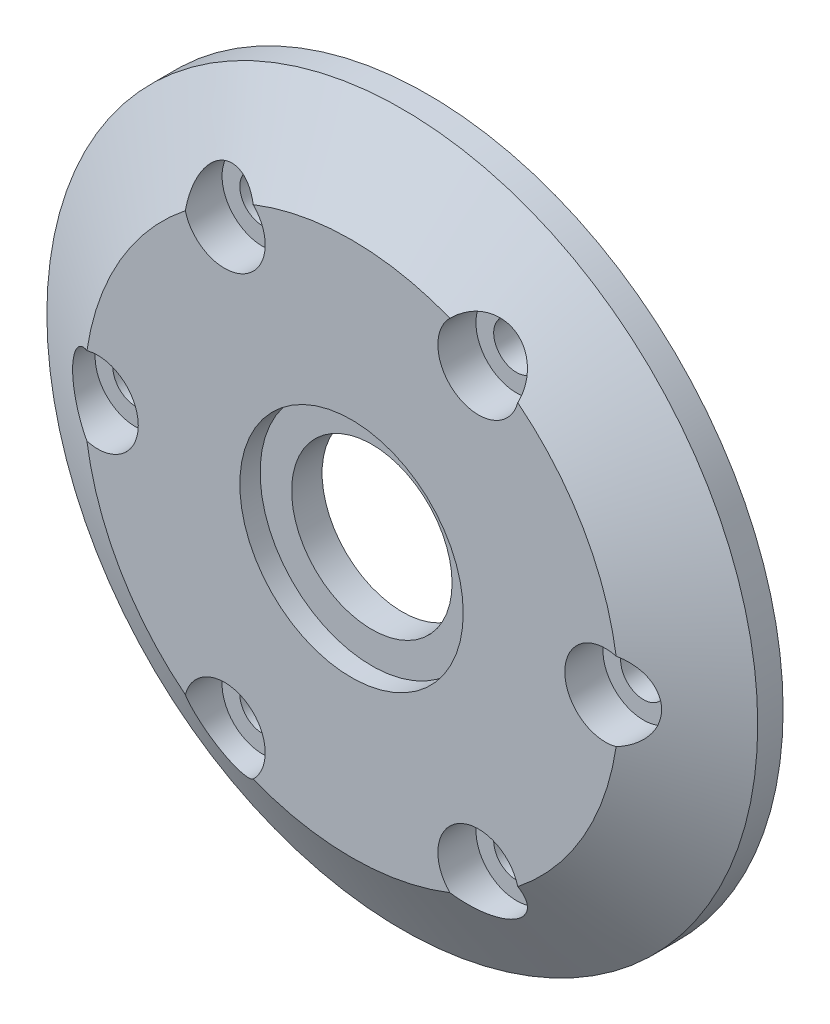
SolidWorks part; units mm, degrees
material "AISI 304"
ref_plane "Front Plane" through (0, 0, 0) normal (0, 0, 1) x (1, 0, 0)
ref_plane "Top Plane" through (0, 0, 0) normal (0, 1, 0) x (1, 0, 0)
ref_plane "Right Plane" through (0, 0, 0) normal (1, 0, 0) x (0, 0, -1)
sketch "Sketch1" plane through (0, 0, 0) normal (0, 0, 1) x (1, 0, 0)
  circle A0 centre (0, 37.5) radius 35
  dimension "D1" = 70
extrude "Boss-Extrude1" add sketch "Sketch1" along normal blind 5 draft 60
sketch "Sketch3" plane through (0, 0, 5) normal (0, 0, 1) x (1, 0, 0)
  circle A0 centre (0, 37.5) radius 11
  dimension "D1" = 22
extrude "Cut-Extrude1" cut sketch "Sketch3" against normal blind 2
sketch "Sketch4" plane through (0, 0, 5) normal (0, 0, 1) x (1, 0, 0)
  circle A0 centre (0, 37.5) radius 7.9
  dimension "D1" = 15.8
extrude "Cut-Extrude2" cut sketch "Sketch4" against normal through all
sketch "Sketch7" plane through (0, 0, 0) normal (0, 0, 1) x (1, 0, 0)
  circle A0 centre (0, 37.5) radius 35 construction
  circle A1 centre (0, 37.5) radius 12.95
  circle A2 centre (0, 37.5) radius 12.95
  circle A3 centre (0, 37.5) radius 35
  dimension "D1" = 0
extrude "Boss-Extrude2" add sketch "Sketch7" against normal blind 2.5
sketch "Sketch5" plane through (0, 0, 0) normal (0, 0, 1) x (1, 0, 0)
  circle A1 centre (-12.5, 15.8494) radius 2.25
  circle A2 centre (-12.5, 15.8494) radius 2.25
  circle A3 centre (-25, 37.5) radius 2.25
  circle A4 centre (-25, 37.5) radius 2.25
  circle A5 centre (-12.5, 59.1506) radius 2.25
  circle A6 centre (-12.5, 59.1506) radius 2.25
  circle A7 centre (12.5, 59.1506) radius 2.25
  circle A8 centre (12.5, 59.1506) radius 2.25
  circle A9 centre (25, 37.5) radius 2.25
  circle A10 centre (25, 37.5) radius 2.25
  circle A11 centre (12.5, 15.8494) radius 2.25
  circle A12 centre (12.5, 15.8494) radius 2.25
  dimension "D1" = 0
  dimension "D2" = 0
  dimension "D3" = 0
  dimension "D4" = 0
  dimension "D5" = 0
  dimension "D6" = 0
extrude "Cut-Extrude6" cut sketch "Sketch5" along normal through all and the other way through all
sketch "Sketch6" plane through (0, 0, 0) normal (0, 0, 1) x (1, 0, 0)
  circle A1 centre (0, 37.5) radius 12.95
  circle A2 centre (0, 37.5) radius 12.95
  circle A3 centre (0, 37.5) radius 11.9
  circle A4 centre (0, 37.5) radius 11.9
  dimension "D1" = 0
  dimension "D2" = 0
extrude "Cut-Extrude7" [suppressed] cut sketch "Sketch6" along normal blind 2.5
sketch "Sketch8" plane through (0, 0, 5) normal (0, 0, 1) x (1, 0, 0)
  circle A1 centre (-12.5, 59.1506) radius 4
  arc A2 (-27.2656, 34.2035) -> (-27.2656, 40.7965) centre (-25, 37.5) ccw
  circle A3 centre (-25, 37.5) radius 4
  circle A4 centre (12.5, 59.1506) radius 4
  circle A5 centre (25, 37.5) radius 4
  circle A6 centre (12.5, 15.8494) radius 4
  circle A7 centre (-12.5, 15.8494) radius 4
  point P15 (0, 37.5)
  dimension "D1" = 1.75
  dimension "D2" = 6
extrude "Cut-Extrude8" cut sketch "Sketch8" against normal blind 3.75
sketch "Sketch9" plane through (0, 0, 0) normal (0, 0, 1) x (1, 0, 0)
  line L0 (-32.311, -8) -> (-32.311, 83) construction
  line L1 (32.311, 83) -> (32.311, -8) construction
  line L2 (-32.311, -8) -> (-32.311, 83)
  line L3 (32.311, 83) -> (32.311, -8)
  line L4 (-32.311, 83) -> (32.311, 83)
  line L5 (32.311, -8) -> (-32.311, -8)
extrude "Cut-Extrude9" [suppressed] cut sketch "Sketch9" against normal through all and the other way through all flip side to cut
